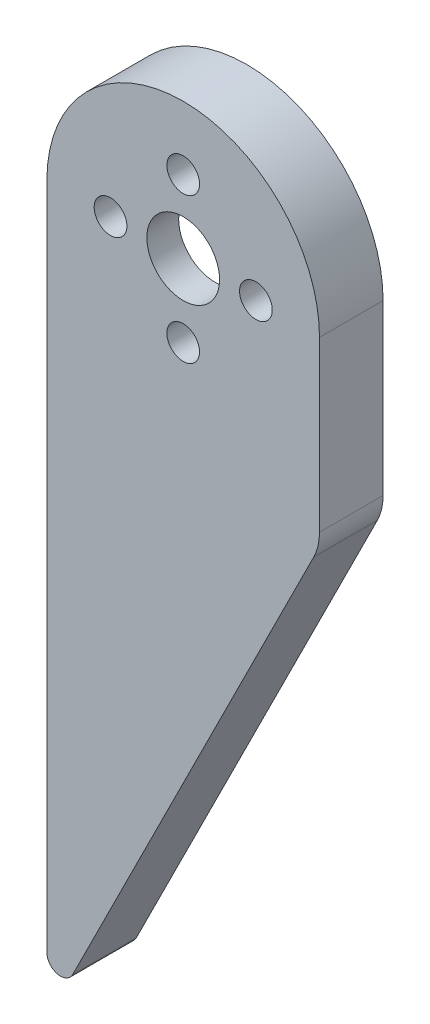
SolidWorks part; units mm, degrees
ref_plane "Plan de face" through (0, 0, 0) normal (0, 0, 1) x (1, 0, 0)
ref_plane "Plan de dessus" through (0, 0, 0) normal (0, 1, 0) x (1, 0, 0)
ref_plane "Plan de droite" through (0, 0, 0) normal (1, 0, 0) x (0, 0, -1)
sketch "Esquisse1" plane through (0, 0, 0) normal (0, 0, 1) x (1, 0, 0)
  line L0 (-15, 0) -> (-15, -80)
  line L1 (15, 0) -> (15, -20)
  line L2 (15, -20) -> (-15, -80)
  circle A0 centre (0, 0) radius 15
  circle A1 centre (0, 0) radius 4
  circle A2 centre (0, 0) radius 8 construction
  circle A3 centre (0, 8) radius 1.8
  circle A4 centre (8, 0) radius 1.8
  circle A5 centre (0, -8) radius 1.8
  circle A6 centre (-8, 0) radius 1.8
extrude "Boss.-Extru.1" add sketch "Esquisse1" along normal blind 7 contours A0 L0 L2 L1 | A0 A6 A5 A4 A3 A1
fillet "Congé1" radius 1.5 1 edges at (-15, -80, 3.5)
fillet "Congé2" radius 6 1 edges at (15, -20, 3.5)
sketch "Esquisse3" plane through (0, 0, 0) normal (0, 0, -1) x (-1, 0, 0)
  circle A0 centre (0, 0) radius 12
extrude "Enlèv. mat.-Extru.2" cut sketch "Esquisse3" against normal blind 3.5
